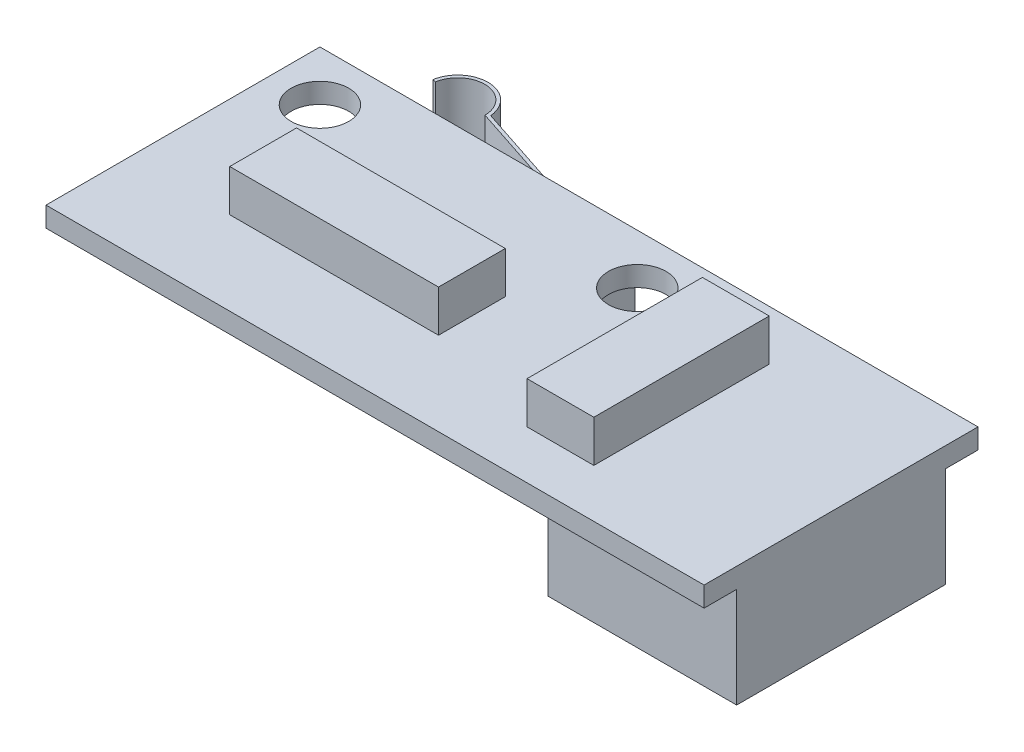
SolidWorks part; units mm, degrees
ref_plane "Front Plane" through (0, 0, 0) normal (0, 0, 1) x (1, 0, 0)
ref_plane "Top Plane" through (0, 0, 0) normal (0, 1, 0) x (1, 0, 0)
ref_plane "Right Plane" through (0, 0, 0) normal (1, 0, 0) x (0, 0, -1)
sketch "Sketch1" plane through (0, 0, 0) normal (0, 1, 0) x (1, 0, 0)
  line L1 (19.7, -8.2) -> (-19.7, -8.2)
  line L2 (19.7, -8.2) -> (19.7, 8.2)
  line L3 (19.7, 8.2) -> (-19.7, 8.2)
  line L4 (-19.7, -8.2) -> (-19.7, 8.2)
  line L5 (0, 8.2) -> (0, -8.2) construction
  line L6 (19.7, 0) -> (-19.7, 0) construction
  circle A0 centre (-16.7, 5.2) radius 1.725
  circle A1 centre (2.3, 5.2) radius 1.725
  point P0 (0, 0)
  point P8 (0, 0)
  dimension "D4" = 3.45
  dimension "D1" = 16.4
  dimension "D2" = 39.4
  dimension "D3" = 19
  dimension "D5" = 3
  dimension "D6" = 3
extrude "Boss-Extrude1" add sketch "Sketch1" along normal blind 1.2
sketch "Sketch2" plane through (0, 1.2, 0) normal (0, 1, 0) x (1, 0, 0)
  line L0 (19.7, -8.2) -> (19.7, 8.2) construction
  line L1 (-13.7, 0.8) -> (-1.2, 0.8)
  line L2 (-13.7, 0.8) -> (-13.7, -3.2)
  line L3 (-13.7, -3.2) -> (-1.2, -3.2)
  line L4 (-1.2, 0.8) -> (-1.2, -3.2)
  line L5 (6.2, 5.2) -> (10.2, 5.2)
  line L6 (6.2, 5.2) -> (6.2, -5.3)
  line L7 (6.2, -5.3) -> (10.2, -5.3)
  line L8 (10.2, 5.2) -> (10.2, -5.3)
  line L9 (19.7, 8.2) -> (-19.7, 8.2) construction
  line L10 (-19.7, 8.2) -> (-19.7, -8.2) construction
  line L11 (-19.7, -8.2) -> (19.7, -8.2) construction
  dimension "D1" = 4
  dimension "D2" = 12.5
  dimension "D3" = 10.5
  dimension "D4" = 9.5
  dimension "D5" = 3
  dimension "D6" = 6
  dimension "D7" = 5
extrude "Boss-Extrude2" add sketch "Sketch2" along normal blind 2.5
sketch "Sketch3" plane through (0, 0, 0) normal (0, -1, 0) x (1, 0, 0)
  line L0 (19.7, 8.2) -> (19.7, -8.2) construction
  line L1 (19.7, 6.25) -> (8.4, 6.25)
  line L2 (19.7, 6.25) -> (19.7, -6.25)
  line L3 (19.7, -6.25) -> (8.4, -6.25)
  line L4 (8.4, 6.25) -> (8.4, -6.25)
  line L5 (19.7, -8.2) -> (-19.7, -8.2) construction
  line L6 (-13.575, -8.2) -> (-0.825, -8.2)
  line L7 (-13.575, -8.2) -> (-13.575, -1.6)
  line L8 (-13.575, -1.6) -> (-0.825, -1.6)
  line L9 (-0.825, -8.2) -> (-0.825, -1.6)
  line L10 (0, 0) -> (8.4, 0) construction
  line L11 (2.3, -5.2) -> (-16.7, -5.2) construction
  line L12 (-7.2, -5.2) -> (-7.2, -1.6) construction
  dimension "D1" = 11.3
  dimension "D2" = 12.5
  dimension "D3" = 6.6
  dimension "D4" = 12.75
extrude "Boss-Extrude3" add sketch "Sketch3" along normal blind 6
ref_plane "Plane1" through (0, -3, 0) normal (0, -1, 0) x (-1, 0, 0)
sketch "Sketch4" plane through (0, -3, 0) normal (0, -1, 0) x (-1, 0, 0)
  line L0 (1.825, 8.2) -> (13.224, 11.95)
  line L1 (13.575, 8.2) -> (0.825, 8.2) construction
  line L2 (9.4425, 13.6) -> (14.0472, 13.6) construction
  line L3 (0.825, 1.6) -> (13.575, 1.6) construction
  line L4 (0.825, 8.2) -> (0.825, 1.6) construction
  line L5 (0.825, 8.2) -> (0.825, 1.6) construction
  line L6 (2.465, 8.2) -> (13.4165, 11.8028)
  line L7 (1.825, 8.2) -> (2.465, 8.2)
  line L8 (16.6277, 12.05) -> (16.825, 12.083)
  line L9 (1.8875, 8.01) -> (13.4165, 11.8028) construction
  arc A0 (13.224, 11.95) -> (16.825, 12.083) centre (15.0331, 11.7832) cw
  arc A1 (13.4165, 11.8028) -> (16.6277, 12.05) centre (15.0331, 11.7832) cw
  dimension "D6" = 1.8168
  dimension "D1" = 12
  dimension "D2" = 3.75
  dimension "D3" = 16
  dimension "D4" = 12
  dimension "D5" = 1
  dimension "D7" = 0.2
extrude "Boss-Extrude4" add sketch "Sketch4" along normal mid plane 4
